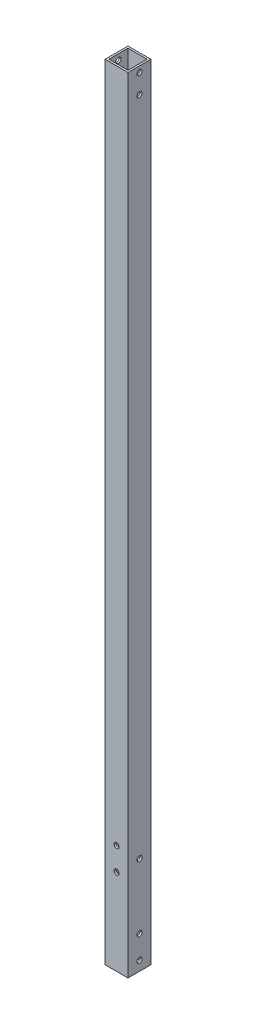
SolidWorks part; units mm, degrees
material "6061 合金"
ref_plane "前视基准面" through (0, 0, 0) normal (0, 0, 1) x (1, 0, 0)
ref_plane "上视基准面" through (0, 0, 0) normal (0, 1, 0) x (1, 0, 0)
ref_plane "右视基准面" through (0, 0, 0) normal (1, 0, 0) x (0, 0, -1)
sketch "草图1" plane through (0, 0, 0) normal (0, 1, 0) x (1, 0, 0)
  line L0 (-5, 5) -> (5, 5)
  line L1 (-6, -6) -> (6, -6)
  line L2 (-6, -6) -> (-6, 6)
  line L3 (-6, 6) -> (6, 6)
  line L4 (6, -6) -> (6, 6)
  line L5 (0, 6) -> (0, -6) construction
  line L6 (-6, 0) -> (6, 0) construction
  line L7 (5, -5) -> (5, 5)
  line L8 (-5, -5) -> (5, -5)
  line L9 (-5, -5) -> (-5, 5)
  point P0 (0, 0)
  dimension "D1" = 12
  dimension "D2" = 1
extrude "凸台-拉伸1" add sketch "草图1" along normal blind 410
sketch "草图2" plane through (6, 0, 0) normal (1, 0, 0) x (0, 0, -1)
  line L0 (0, 0) -> (0, 410) construction
  line L1 (-6, 0) -> (6, 0) construction
  line L2 (-6, 410) -> (6, 410) construction
  circle A0 centre (0, 5) radius 1.35
  circle A1 centre (0, 17) radius 1.35
  circle A2 centre (0, 51) radius 1.35
  dimension "D1" = 5
  dimension "D2" = 12
  dimension "D3" = 2.7
  dimension "D4" = 51
extrude "切除-拉伸1" cut sketch "草图2" against normal through all
sketch "草图3" plane through (6, 0, 0) normal (1, 0, 0) x (0, 0, -1)
  line L0 (0, 410) -> (0, 407) construction
  line L1 (-6, 410) -> (6, 410) construction
  circle A0 centre (0, 407) radius 1.35
  circle A1 centre (0, 397) radius 1.35
  dimension "D1" = 2.7
  dimension "D3" = 10
  dimension "D2" = 3
extrude "切除-拉伸2" cut sketch "草图3" against normal through all
sketch "草图4" plane through (0, 0, -6) normal (0, 0, -1) x (-1, 0, 0)
  line L0 (0, 0) -> (0, 410) construction
  line L1 (-6, 410) -> (6, 410) construction
  line L2 (-6, 0) -> (6, 0) construction
  circle A0 centre (0, 45) radius 1.35
  circle A1 centre (0, 57) radius 1.35
  dimension "D1" = 12
  dimension "D3" = 2.7
  dimension "D2" = 45
extrude "切除-拉伸3" cut sketch "草图4" against normal through all
